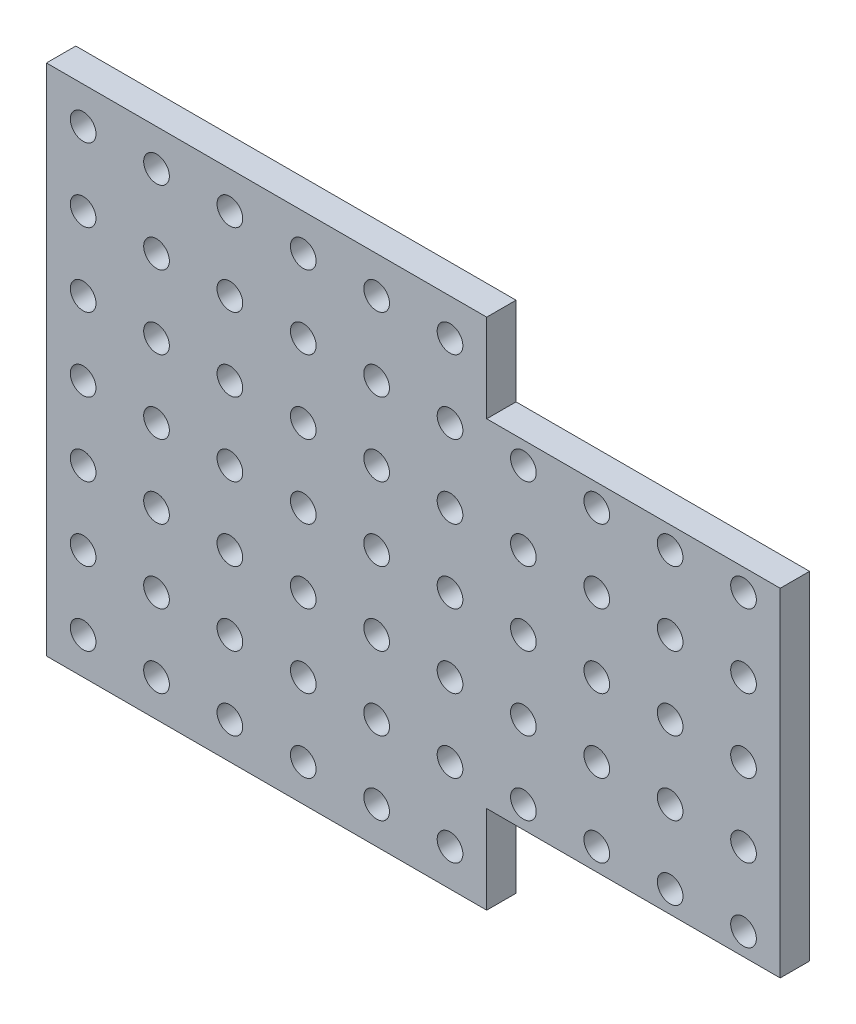
SolidWorks part; units mm, degrees
ref_plane "Plan de face" through (0, 0, 0) normal (0, 0, 1) x (1, 0, 0)
ref_plane "Plan de dessus" through (0, 0, 0) normal (0, 1, 0) x (1, 0, 0)
ref_plane "Plan de droite" through (0, 0, 0) normal (1, 0, 0) x (0, 0, -1)
sketch "Esquisse1" plane through (0, 0, 0) normal (0, 0, 1) x (1, 0, 0)
  line L0 (5, 70) -> (5, 0) construction
  line L1 (0, 0) -> (100, 0) construction
  line L2 (0, 0) -> (0, 70)
  line L3 (0, 70) -> (100, 70) construction
  line L4 (100, 0) -> (100, 70) construction
  line L5 (0, 5) -> (100, 5) construction
  line L6 (0, 0) -> (60, 0)
  line L7 (60, 0) -> (60, 12)
  line L8 (60, 12) -> (100, 12)
  line L9 (100, 12) -> (100, 58)
  line L10 (100, 58) -> (60, 58)
  line L11 (60, 58) -> (60, 70)
  line L12 (60, 70) -> (0, 70)
  circle A0 centre (5, 5) radius 1.75
  circle A1 centre (15, 5) radius 1.75
  circle A2 centre (25, 5) radius 1.75
  circle A3 centre (35, 5) radius 1.75
  circle A4 centre (45, 5) radius 1.75
  circle A5 centre (55, 5) radius 1.75
  circle A6 centre (65, 5) radius 1.75 construction
  circle A7 centre (75, 5) radius 1.75 construction
  circle A8 centre (85, 5) radius 1.75 construction
  circle A9 centre (95, 5) radius 1.75 construction
  circle A10 centre (15, 15) radius 1.75
  circle A11 centre (25, 15) radius 1.75
  circle A12 centre (35, 15) radius 1.75
  circle A13 centre (45, 15) radius 1.75
  circle A14 centre (55, 15) radius 1.75
  circle A15 centre (65, 15) radius 1.75
  circle A16 centre (75, 15) radius 1.75
  circle A17 centre (85, 15) radius 1.75
  circle A18 centre (95, 15) radius 1.75
  circle A19 centre (15, 25) radius 1.75
  circle A20 centre (25, 25) radius 1.75
  circle A21 centre (35, 25) radius 1.75
  circle A22 centre (45, 25) radius 1.75
  circle A23 centre (55, 25) radius 1.75
  circle A24 centre (65, 25) radius 1.75
  circle A25 centre (75, 25) radius 1.75
  circle A26 centre (85, 25) radius 1.75
  circle A27 centre (95, 25) radius 1.75
  circle A28 centre (15, 35) radius 1.75
  circle A29 centre (25, 35) radius 1.75
  circle A30 centre (35, 35) radius 1.75
  circle A31 centre (45, 35) radius 1.75
  circle A32 centre (55, 35) radius 1.75
  circle A33 centre (65, 35) radius 1.75
  circle A34 centre (75, 35) radius 1.75
  circle A35 centre (85, 35) radius 1.75
  circle A36 centre (95, 35) radius 1.75
  circle A37 centre (15, 45) radius 1.75
  circle A38 centre (25, 45) radius 1.75
  circle A39 centre (35, 45) radius 1.75
  circle A40 centre (45, 45) radius 1.75
  circle A41 centre (55, 45) radius 1.75
  circle A42 centre (65, 45) radius 1.75
  circle A43 centre (75, 45) radius 1.75
  circle A44 centre (85, 45) radius 1.75
  circle A45 centre (95, 45) radius 1.75
  circle A46 centre (15, 55) radius 1.75
  circle A47 centre (25, 55) radius 1.75
  circle A48 centre (35, 55) radius 1.75
  circle A49 centre (45, 55) radius 1.75
  circle A50 centre (55, 55) radius 1.75
  circle A51 centre (65, 55) radius 1.75
  circle A52 centre (75, 55) radius 1.75
  circle A53 centre (85, 55) radius 1.75
  circle A54 centre (95, 55) radius 1.75
  circle A55 centre (15, 65) radius 1.75
  circle A56 centre (25, 65) radius 1.75
  circle A57 centre (35, 65) radius 1.75
  circle A58 centre (45, 65) radius 1.75
  circle A59 centre (55, 65) radius 1.75
  circle A60 centre (65, 65) radius 1.75 construction
  circle A61 centre (75, 65) radius 1.75 construction
  circle A62 centre (85, 65) radius 1.75 construction
  circle A63 centre (95, 65) radius 1.75 construction
  circle A64 centre (5, 15) radius 1.75
  circle A65 centre (5, 25) radius 1.75
  circle A66 centre (5, 35) radius 1.75
  circle A67 centre (5, 45) radius 1.75
  circle A68 centre (5, 55) radius 1.75
  circle A69 centre (5, 65) radius 1.75
  dimension "D5" = 3.5
  dimension "D1" = 70
  dimension "D2" = 100
  dimension "D3" = 5
  dimension "D4" = 5
  dimension "D8" = 40
  dimension "D9" = 12
  dimension "D10" = 12
  dimension "D6" = 10
  dimension "D7" = 7
extrude "Boss.-Extru.1" add sketch "Esquisse1" along normal blind 4
